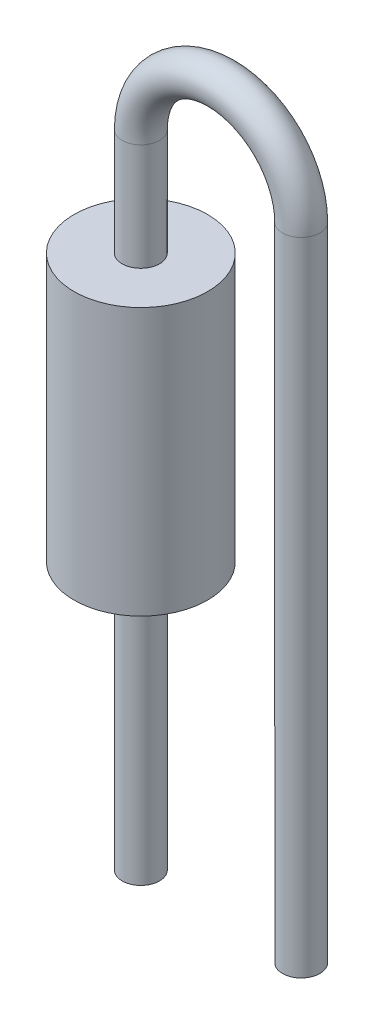
SolidWorks part; units mm, degrees
ref_plane "Спереди" through (0, 0, 0) normal (0, 0, 1) x (1, 0, 0)
ref_plane "Сверху" through (0, 0, 0) normal (0, 1, 0) x (1, 0, 0)
ref_plane "Справа" through (0, 0, 0) normal (1, 0, 0) x (0, 0, -1)
sketch "Эскиз1" plane through (0, 0, 0) normal (0, 0, 1) x (1, 0, 0)
  line L0 (-31.2904, 0) -> (32.9593, 0) construction
  line L1 (0, 0) -> (0, 12)
  line L2 (3, 12) -> (3, 0)
  arc A0 (0, 12) -> (3, 12) centre (1.5, 12) cw
  dimension "D1" = 1.5
  dimension "D2" = 12
sketch "Эскиз2" plane through (0, 0, 0) normal (0, 1, 0) x (1, 0, 0)
  circle A0 centre (0, 0) radius 0.35
  dimension "D1" = 0.7
sweep "По траектории1" add profiles "Эскиз2" path "Эскиз1"
ref_plane "Плоскость1" through (0, 5, 0) normal (0, -1, 0) x (1, 0, 0)
sketch "Эскиз3" plane through (0, 5, 0) normal (0, -1, 0) x (1, 0, 0)
  circle A0 centre (0, 0) radius 1.25
  dimension "D1" = 2.5
extrude "Вытянуть1" add sketch "Эскиз3" against normal blind 5
